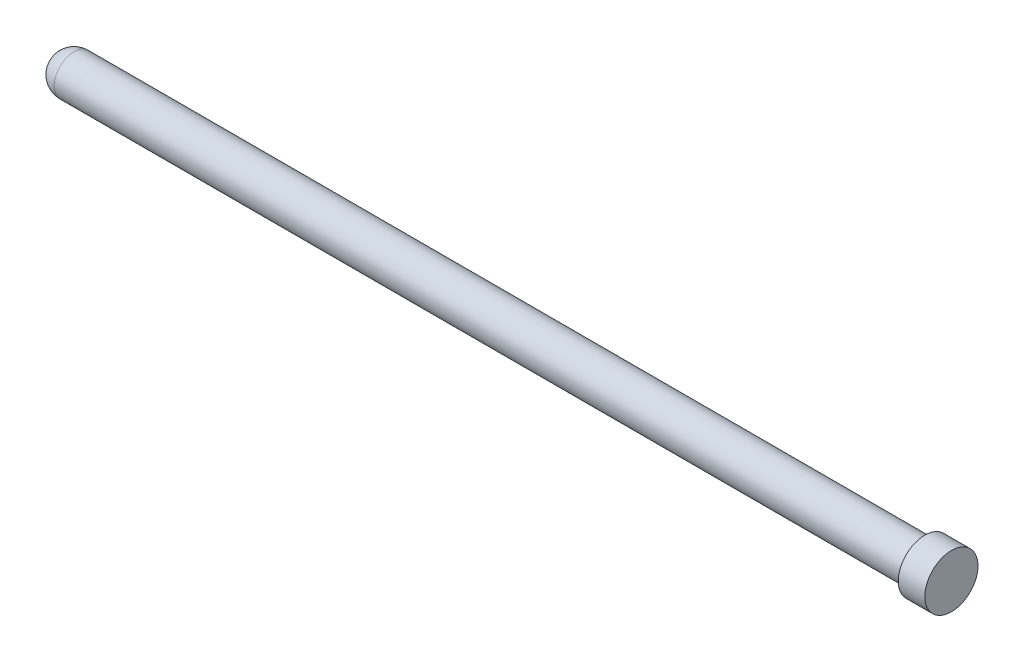
SolidWorks part; units mm, degrees
ref_plane "Front Plane" through (0, 0, 0) normal (0, 0, 1) x (1, 0, 0)
ref_plane "Top Plane" through (0, 0, 0) normal (0, 1, 0) x (1, 0, 0)
ref_plane "Right Plane" through (0, 0, 0) normal (1, 0, 0) x (0, 0, -1)
sketch "Sketch1" plane through (0, 0, 0) normal (1, 0, 0) x (0, 0, -1)
  circle A0 centre (0, 0) radius 9.525
  dimension "D1" = 19.05
extrude "Boss-Extrude1" add sketch "Sketch1" along normal blind 406.4
sketch "Sketch2" plane through (0, 0, 0) normal (0, 0, 1) x (1, 0, 0)
  line L0 (0, 9.525) -> (0, -9.525) construction
  line L1 (-9.525, 0) -> (0, 0)
  line L2 (0, 0) -> (0, 9.525)
  arc A0 (0, 9.525) -> (-9.525, 0) centre (0, 0) ccw
revolve "Revolve1" add sketch "Sketch2" angle 360 about L1
sketch "Sketch3" plane through (406.4, 0, 0) normal (1, 0, 0) x (0, 0, -1)
  circle A0 centre (0, 0) radius 12.7
  dimension "D1" = 25.4
extrude "Boss-Extrude2" add sketch "Sketch3" along normal blind 12.7
